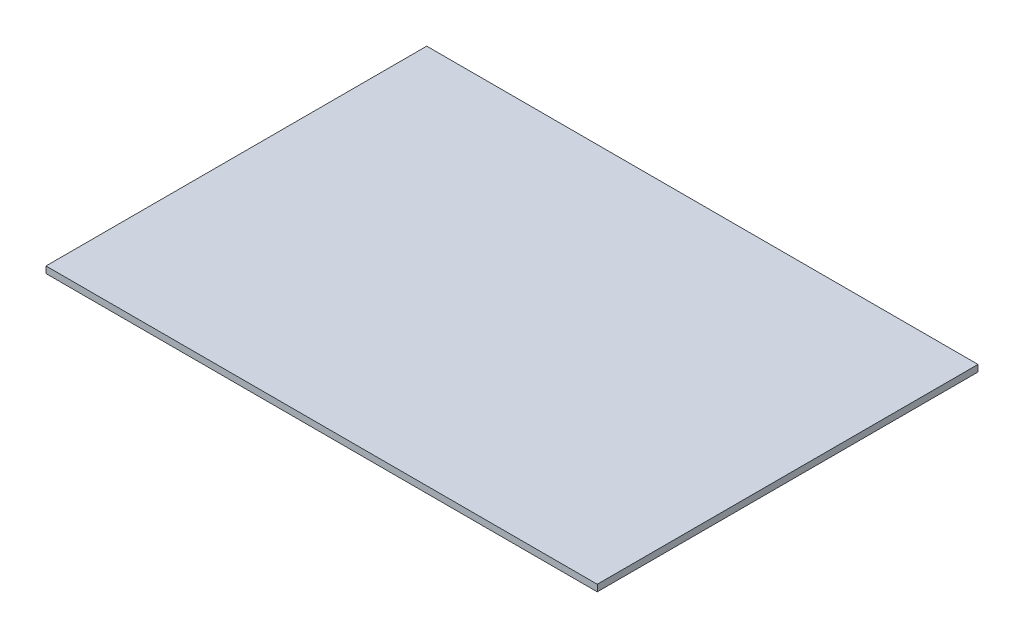
SolidWorks part; units mm, degrees
ref_plane "Front Plane" through (0, 0, 0) normal (0, 0, 1) x (1, 0, 0)
ref_plane "Top Plane" through (0, 0, 0) normal (0, 1, 0) x (1, 0, 0)
ref_plane "Right Plane" through (0, 0, 0) normal (1, 0, 0) x (0, 0, -1)
sketch "Esquisse1" plane through (0, 0, 0) normal (0, 1, 0) x (1, 0, 0)
  line L1 (-750, 518) -> (750, 518)
  line L2 (-750, 518) -> (-750, -518)
  line L3 (-750, -518) -> (750, -518)
  line L4 (750, 518) -> (750, -518)
  line L5 (-750, 518) -> (750, -518) construction
  line L6 (-750, -518) -> (750, 518) construction
  point P0 (0, 0)
extrude "Boss.-Extru.1" add sketch "Esquisse1" along normal blind 18
